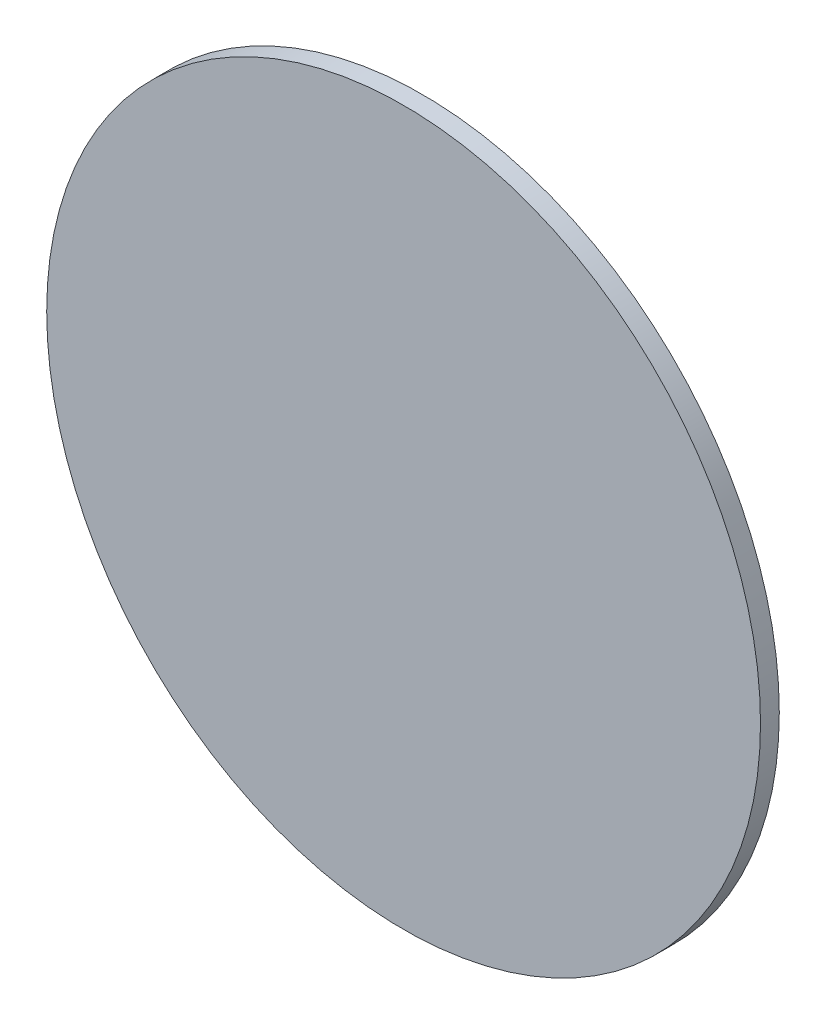
SolidWorks part; units mm, degrees
ref_plane "Спереди" through (0, 0, 0) normal (0, 0, 1) x (1, 0, 0)
ref_plane "Сверху" through (0, 0, 0) normal (0, 1, 0) x (1, 0, 0)
ref_plane "Справа" through (0, 0, 0) normal (1, 0, 0) x (0, 0, -1)
sketch "Эскиз1" plane through (0, 0, 0) normal (0, 0, 1) x (1, 0, 0)
  circle A0 centre (0, 0) radius 19
  dimension "D1" = 38
extrude "Бобышка-Вытянуть1" add sketch "Эскиз1" along normal blind 1
